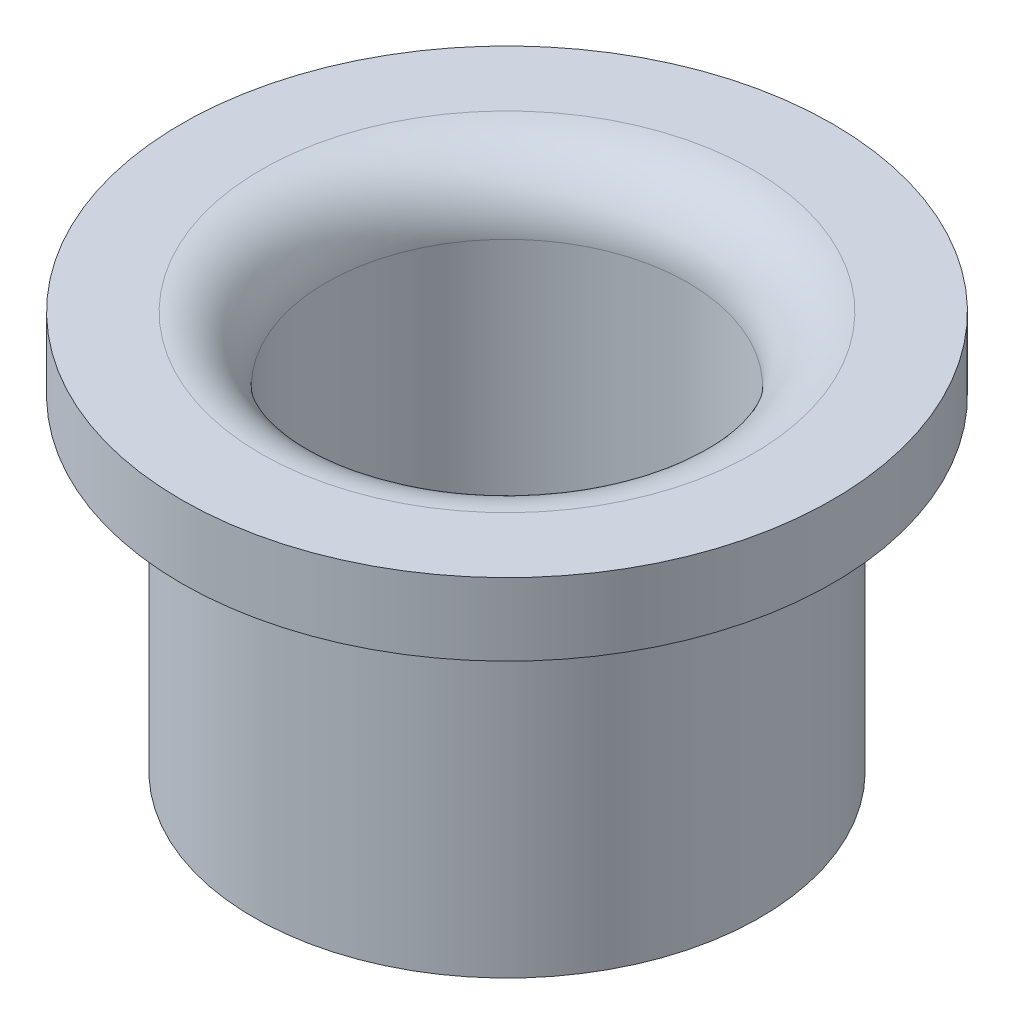
SolidWorks part; units mm, degrees
ref_plane "Plan1" through (0, 0, 0) normal (0, 0, 1) x (1, 0, 0)
ref_plane "Plan2" through (0, 0, 0) normal (0, 1, 0) x (1, 0, 0)
ref_plane "Plan3" through (0, 0, 0) normal (1, 0, 0) x (0, 0, -1)
sketch "Esquisse1" plane through (0, 0, 0) normal (0, 0, 1) x (1, 0, 0)
  line L0 (0, 0) -> (0, 190) construction
  line L1 (5, 0) -> (5, 9.2)
  line L2 (6.8, 11) -> (9, 11)
  line L3 (9, 11) -> (9, 9)
  line L4 (9, 9) -> (7.8, 9)
  line L5 (7, 8.2) -> (7, 0)
  line L6 (7, 0) -> (5, 0)
  arc A0 (7, 8.2) -> (7.8, 9) centre (7.8, 8.2) cw
  arc A1 (5, 9.2) -> (6.8, 11) centre (6.8, 9.2) cw
  dimension "D6" = 0.8
  dimension "D7" = 1.8
  dimension "D1" = 5
  dimension "D2" = 2
  dimension "D3" = 2
  dimension "D4" = 9
  dimension "D5" = 9
revolve "Base-Révolution" add sketch "Esquisse1" angle 360 about L0
